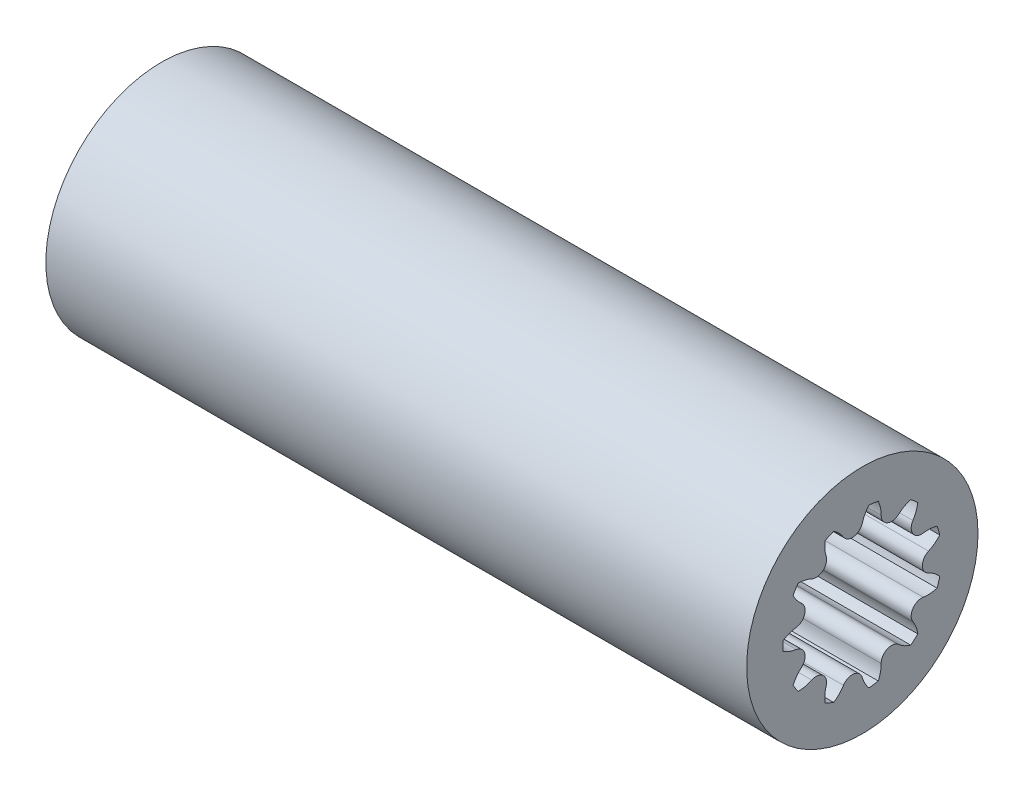
SolidWorks part; units mm, degrees
ref_plane "Front Plane" through (0, 0, 0) normal (1, 0, 0) x (0, 1, 0)
ref_plane "Top Plane" through (0, 0, 0) normal (0, 0, 1) x (0, 1, 0)
ref_plane "Right Plane" through (0, 0, 0) normal (0, 1, 0) x (-1, 0, 0)
sketch "Sketch1" plane through (0, 0, 0) normal (1, 0, 0) x (0, 1, 0)
  line L0 (-2.0767, 2.5) -> (2.0767, 2.5)
  circle A0 centre (0, 0) radius 3.25 construction
  circle A1 centre (0, 0) radius 5.5
  circle A2 centre (0, 0) radius 3.05
  dimension "D1" = 0.2
  dimension "D2" = 6.1
  dimension "D4" = 11
  dimension "D3" = 2.5
extrude "Boss-Extrude1" add sketch "Sketch1" along normal blind 14
sketch "Sketch2" plane through (14, 0, 0) normal (1, 0, 0) x (0, 1, 0)
  circle A0 centre (0, 0) radius 5.5
  circle A1 centre (0, 0) radius 5.5 construction
extrude "Boss-Extrude2" add sketch "Sketch2" along normal blind 13.52
sketch "Sketch3" plane through (27.52, 0, 0) normal (1, 0, 0) x (0, 1, 0)
  circle A0 centre (0, 0) radius 3.84 construction
  arc A1 (-1.322, -2.893) -> (-1.3171, -2.8446) centre (-1.8115, -2.8187) ccw
  arc A2 (-0.4299, -3.1051) -> (-0.4519, -3.1485) centre (0, -3.3506) ccw
  arc A3 (0.4299, -3.1051) -> (-0.4299, -3.1051) centre (0, -3.3506) ccw
  arc A4 (0.4519, -3.1485) -> (0.4299, -3.1051) centre (0, -3.3506) ccw
  arc A5 (1.3171, -2.8446) -> (1.322, -2.893) centre (1.8115, -2.8187) ccw
  arc A6 (2.0824, -2.4044) -> (2.0404, -2.3797) centre (1.8115, -2.8187) ccw
  arc A7 (3.0517, -0.8968) -> (3.0031, -0.8989) centre (3.0478, -1.3919) ccw
  arc A8 (2.6459, -1.6809) -> (2.6762, -1.719) centre (3.0478, -1.3919) ccw
  arc A9 (3.1347, 0.0164) -> (3.1808, 0.0008) centre (3.3165, 0.4768) ccw
  arc A10 (3.0521, 0.8954) -> (3.0123, 0.8674) centre (3.3165, 0.4768) ccw
  arc A11 (3.0517, -0.8968) -> (3.7011, -0.7578) centre (3.0638, 0.6324) ccw
  arc A12 (3.0031, -0.8989) -> (2.6459, -1.6809) centre (3.0478, -1.3919) ccw
  arc A13 (2.9964, -2.3008) -> (2.6762, -1.719) centre (1.5285, -2.7296) ccw
  arc A14 (2.7039, -2.6385) -> (2.9964, -2.3008) centre (0, 0) ccw
  arc A15 (2.0824, -2.4044) -> (2.7039, -2.6385) centre (2.9193, -1.1245) ccw
  arc A16 (2.0404, -2.3797) -> (1.3171, -2.8446) centre (1.8115, -2.8187) ccw
  arc A17 (1.2768, -3.5556) -> (1.322, -2.893) centre (-0.1899, -3.1226) ccw
  arc A18 (0.8482, -3.6814) -> (1.2768, -3.5556) centre (0, 0) ccw
  arc A19 (0.4519, -3.1485) -> (0.8482, -3.6814) centre (1.848, -2.5243) ccw
  arc A20 (-0.8482, -3.6814) -> (-0.4519, -3.1485) centre (-1.848, -2.5243) ccw
  arc A21 (-1.2768, -3.5556) -> (-0.8482, -3.6814) centre (0, 0) ccw
  arc A22 (-1.322, -2.893) -> (-1.2768, -3.5556) centre (0.1899, -3.1226) ccw
  arc A23 (3.7011, -0.7578) -> (3.7647, -0.3156) centre (0, 0) ccw
  arc A24 (3.7647, -0.3156) -> (3.1808, 0.0008) centre (2.7616, -1.4699) ccw
  arc A25 (3.0123, 0.8674) -> (3.1347, 0.0164) centre (3.3165, 0.4768) ccw
  arc A26 (3.0521, 0.8954) -> (3.5232, 1.3635) centre (2.2356, 2.1884) ccw
  arc A27 (3.5232, 1.3635) -> (3.3377, 1.7698) centre (0, 0) ccw
  arc A28 (-2.0404, -2.3797) -> (-2.0824, -2.4044) centre (-1.8115, -2.8187) ccw
  arc A29 (-2.6762, -1.719) -> (-2.6459, -1.6809) centre (-3.0478, -1.3919) ccw
  arc A30 (-3.0031, -0.8989) -> (-3.0517, -0.8968) centre (-3.0478, -1.3919) ccw
  arc A31 (-3.1808, 0.0008) -> (-3.1347, 0.0164) centre (-3.3165, 0.4768) ccw
  arc A32 (-3.0123, 0.8674) -> (-3.0521, 0.8954) centre (-3.3165, 0.4768) ccw
  arc A33 (-1.3171, -2.8446) -> (-2.0404, -2.3797) centre (-1.8115, -2.8187) ccw
  arc A34 (-2.7039, -2.6385) -> (-2.0824, -2.4044) centre (-2.9193, -1.1245) ccw
  arc A35 (-2.9964, -2.3008) -> (-2.7039, -2.6385) centre (0, 0) ccw
  arc A36 (-2.6762, -1.719) -> (-2.9964, -2.3008) centre (-1.5285, -2.7296) ccw
  arc A37 (-2.6459, -1.6809) -> (-3.0031, -0.8989) centre (-3.0478, -1.3919) ccw
  arc A38 (-3.7011, -0.7578) -> (-3.0517, -0.8968) centre (-3.0638, 0.6324) ccw
  arc A39 (-3.7647, -0.3156) -> (-3.7011, -0.7578) centre (0, 0) ccw
  arc A40 (-3.1808, 0.0008) -> (-3.7647, -0.3156) centre (-2.7616, -1.4699) ccw
  arc A41 (-3.1347, 0.0164) -> (-3.0123, 0.8674) centre (-3.3165, 0.4768) ccw
  arc A42 (-3.5232, 1.3635) -> (-3.0521, 0.8954) centre (-2.2356, 2.1884) ccw
  arc A43 (-2.6754, 1.7203) -> (-2.6282, 1.7085) centre (-2.5322, 2.1942) ccw
  arc A44 (-2.0651, 2.3583) -> (-2.0835, 2.4034) centre (-2.5322, 2.1942) ccw
  arc A45 (-1.3207, 2.8936) -> (-1.2873, 2.8582) centre (-0.944, 3.2148) ccw
  arc A46 (-0.4623, 3.1004) -> (-0.4534, 3.1483) centre (-0.944, 3.2148) ccw
  arc A47 (2.6282, 1.7085) -> (2.6754, 1.7203) centre (2.5322, 2.1942) ccw
  arc A48 (2.0835, 2.4034) -> (2.0651, 2.3583) centre (2.5322, 2.1942) ccw
  arc A49 (3.3377, 1.7698) -> (2.6754, 1.7203) centre (3.1179, 0.2564) ccw
  arc A50 (2.0651, 2.3583) -> (2.6282, 1.7085) centre (2.5322, 2.1942) ccw
  arc A51 (2.0835, 2.4034) -> (2.2268, 3.0518) centre (0.6976, 3.0497) ccw
  arc A52 (2.2268, 3.0518) -> (1.851, 3.2933) centre (0, 0) ccw
  arc A53 (1.2873, 2.8582) -> (1.3207, 2.8936) centre (0.944, 3.2148) ccw
  arc A54 (0.4534, 3.1483) -> (0.4623, 3.1004) centre (0.944, 3.2148) ccw
  arc A55 (1.851, 3.2933) -> (1.3207, 2.8936) centre (2.4843, 1.9014) ccw
  arc A56 (0.4623, 3.1004) -> (1.2873, 2.8582) centre (0.944, 3.2148) ccw
  arc A57 (0.4534, 3.1483) -> (0.2234, 3.7713) centre (-1.0619, 2.9427) ccw
  arc A58 (0.2234, 3.7713) -> (0, 3.7779) centre (0, 0) ccw
  arc A59 (0, 3.7779) -> (-0.2234, 3.7713) centre (0, 0) ccw
  arc A60 (-0.2234, 3.7713) -> (-0.4534, 3.1483) centre (1.0619, 2.9427) ccw
  arc A61 (-1.2873, 2.8582) -> (-0.4623, 3.1004) centre (-0.944, 3.2148) ccw
  arc A62 (-1.3207, 2.8936) -> (-1.851, 3.2933) centre (-2.4843, 1.9014) ccw
  arc A63 (-1.851, 3.2933) -> (-2.2268, 3.0518) centre (0, 0) ccw
  arc A64 (-2.2268, 3.0518) -> (-2.0835, 2.4034) centre (-0.6976, 3.0497) ccw
  arc A65 (-2.6282, 1.7085) -> (-2.0651, 2.3583) centre (-2.5322, 2.1942) ccw
  arc A66 (-2.6754, 1.7203) -> (-3.3377, 1.7698) centre (-3.1179, 0.2564) ccw
  arc A67 (-3.3377, 1.7698) -> (-3.5232, 1.3635) centre (0, 0) ccw
  circle A68 centre (0, 0) radius 5.5
  circle A69 centre (0, 0) radius 5.5 construction
  point P3 (0, 1.6)
extrude "Boss-Extrude3" add sketch "Sketch3" along normal blind 5.8
sketch "Sketch4" plane through (27.52, 0, 0) normal (1, 0, 0) x (0, 1, 0)
  circle A0 centre (0, 0) radius 1.05
  dimension "D1" = 2.1
extrude "Cut-Extrude1" cut sketch "Sketch4" against normal blind 3.5
